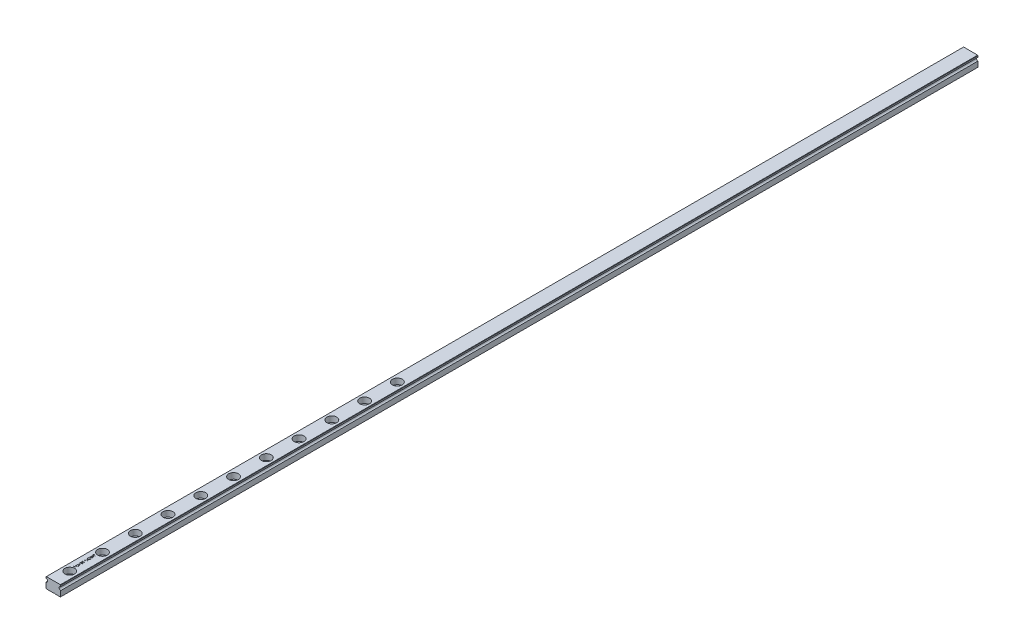
SolidWorks part; units mm, degrees
material "镀铬不锈钢"
ref_plane "前视基准面" through (0, 0, 0) normal (0, 0, 1) x (1, 0, 0)
ref_plane "上视基准面" through (0, 0, 0) normal (0, 1, 0) x (1, 0, 0)
ref_plane "右视基准面" through (0, 0, 0) normal (1, 0, 0) x (0, 0, -1)
sketch "草图1" plane through (0, 0, 0) normal (0, 0, 1) x (1, 0, 0)
  line L2 (4.5, 5.5) -> (4.5, 6.3)
  line L3 (-4.3, 6.5) -> (-4.5, 6.3)
  line L4 (4.5, 0.2) -> (4.5, 3.5)
  line L5 (4.3, 6.5) -> (-4.3, 6.5)
  line L6 (4.5, 6.3) -> (4.3, 6.5)
  line L7 (-4.3, 0) -> (0.2, 0)
  line L8 (4.3, 0) -> (4.5, 0.2)
  line L9 (0.8, 0) -> (4.3, 0)
  line L10 (-4.5, 0.2) -> (-4.3, 0)
  line L11 (0, 6.5) -> (0, 0) construction
  line L12 (-4.5, 3.5) -> (-4.5, 0.2)
  line L13 (-4.5, 6.3) -> (-4.5, 5.5)
  arc A0 (-4.5, 3.5) -> (-4.5, 5.5) centre (-4.5, 4.5) ccw
  arc A1 (0.8, 0) -> (0.2, 0) centre (0.5, 0) ccw
  arc A2 (4.5, 5.5) -> (4.5, 3.5) centre (4.5, 4.5) ccw
extrude "凸台-拉伸1" add sketch "草图1" against normal blind 220
hole_wizard "M3 六角凹头螺钉的柱形沉头孔1" positions "草图3" profile "草图2" counterbore size "M3" standard "ISO" end condition through all
sketch "草图3" plane through (0.7549, 6.5, 19.3435) normal (0, 1, 0) x (-1, 0, 0)
  point P0 (0.7549, -29.3435)
  dimension "D1" = 10
sketch "草图2" plane through (0, 6.5, -10) normal (1, 0, 0) x (0, 0, 1)
  line L0 (0, 0) -> (0, 6.5)
  line L1 (0, 6.5) -> (1.75, 6.5)
  line L3 (1.75, 6.5) -> (1.75, 3.5)
  line L4 (1.75, 3.5) -> (3, 3.5)
  line L5 (3, 3.5) -> (3, 0)
  line L7 (3, 0) -> (0, 0)
  line L11 (0, -6.35) -> (0, 107.95) construction
  dimension "通孔孔直径" = 3.5
  dimension "通孔孔深度" = 6.5
  dimension "柱形沉头孔直径" = 6
  dimension "柱形沉头孔深度" = 3.5
pattern_linear "阵列(线性)1" count 11 spacing 20 along (0, 0, -1) of "M3 六角凹头螺钉的柱形沉头孔1"
sketch "草图6" plane through (0, 6.5, 0) normal (0, 1, 0) x (1, 0, 0)
  line L0 (0, 10) -> (0, 30) construction
  text T0 "HIWIN MGN9" font "Century Gothic" height 1.5
extrude "切除-拉伸1" cut sketch "草图6" against normal blind 0.1
sketch "草图7" plane through (0, 0, -220) normal (0, 0, -1) x (-1, 0, 0)
  line L11 (-4.3, 0) -> (-0.8, 0)
  line L12 (-0.2, 0) -> (4.3, 0)
  line L13 (4.3, 0) -> (4.5, 0.2)
  line L14 (4.5, 0.2) -> (4.5, 3.5)
  line L15 (4.5, 5.5) -> (4.5, 6.3)
  line L16 (4.5, 6.3) -> (4.3, 6.5)
  line L17 (4.3, 6.5) -> (-4.3, 6.5)
  line L18 (-4.3, 6.5) -> (-4.5, 6.3)
  line L19 (-4.5, 6.3) -> (-4.5, 5.5)
  line L20 (-4.5, 3.5) -> (-4.5, 0.2)
  line L21 (-4.5, 0.2) -> (-4.3, 0)
  line L22 (-4.3, 0) -> (-0.8, 0)
  line L23 (-0.2, 0) -> (4.3, 0)
  line L24 (4.3, 0) -> (4.5, 0.2)
  line L25 (4.5, 0.2) -> (4.5, 3.5)
  line L26 (4.5, 5.5) -> (4.5, 6.3)
  line L27 (4.5, 6.3) -> (4.3, 6.5)
  line L28 (4.3, 6.5) -> (-4.3, 6.5)
  line L29 (-4.3, 6.5) -> (-4.5, 6.3)
  line L30 (-4.5, 6.3) -> (-4.5, 5.5)
  line L31 (-4.5, 3.5) -> (-4.5, 0.2)
  line L32 (-4.5, 0.2) -> (-4.3, 0)
  arc A3 (-0.2, 0) -> (-0.8, 0) centre (-0.5, 0) ccw
  arc A4 (4.5, 5.5) -> (4.5, 3.5) centre (4.5, 4.5) ccw
  arc A5 (-4.5, 3.5) -> (-4.5, 5.5) centre (-4.5, 4.5) ccw
  arc A6 (-0.2, 0) -> (-0.8, 0) centre (-0.5, 0) ccw
  arc A7 (4.5, 5.5) -> (4.5, 3.5) centre (4.5, 4.5) ccw
  arc A8 (-4.5, 3.5) -> (-4.5, 5.5) centre (-4.5, 4.5) ccw
  dimension "D1" = 0
extrude "凸台-拉伸2" add sketch "草图7" along normal blind 340
